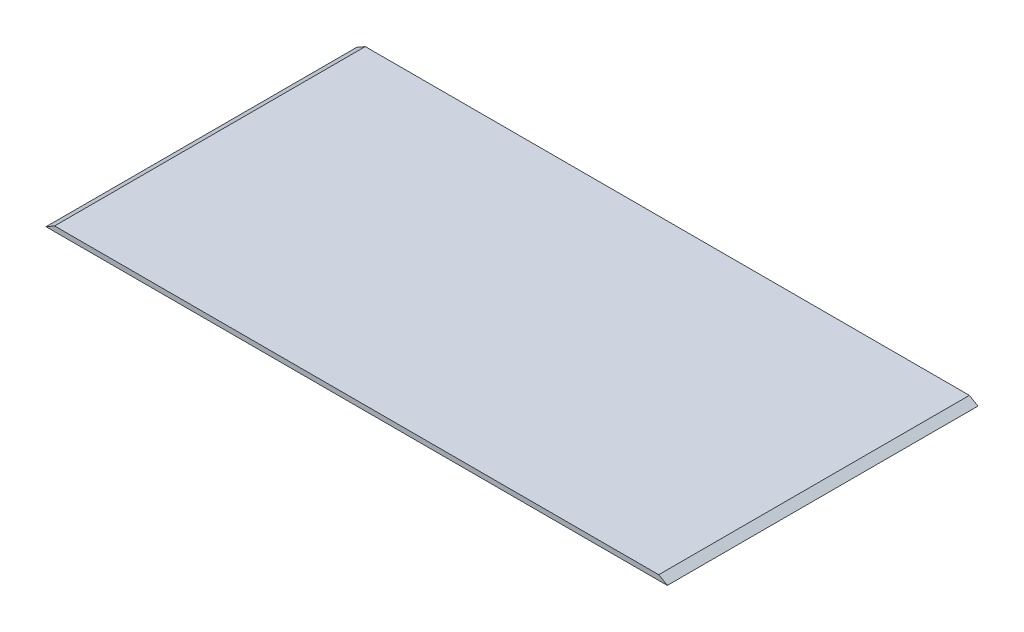
SolidWorks part; units mm, degrees
ref_plane "前视基准面" through (0, 0, 0) normal (0, 0, 1) x (1, 0, 0)
ref_plane "上视基准面" through (0, 0, 0) normal (0, 1, 0) x (1, 0, 0)
ref_plane "右视基准面" through (0, 0, 0) normal (1, 0, 0) x (0, 0, -1)
sketch "草图1" plane through (0, 0, 0) normal (0, 1, 0) x (1, 0, 0)
  line L1 (-125, -125) -> (125, -125)
  line L2 (-125, -125) -> (-125, 125)
  line L3 (-125, 125) -> (125, 125)
  line L4 (125, -125) -> (125, 125)
  line L5 (-125, -125) -> (125, 125) construction
  line L6 (-125, 125) -> (125, -125) construction
  point P0 (0, 0)
  dimension "D1" = 250
  dimension "D2" = 250
extrude "凸台-拉伸1" add sketch "草图1" along normal blind 2
sketch "草图2" plane through (0, 2, 0) normal (0, 1, 0) x (1, 0, 0)
  line L0 (-125, 0) -> (125, 0)
  line L4 (125, -125) -> (125, 125)
  line L5 (125, 125) -> (-125, 125)
  line L6 (-125, 125) -> (-125, -125)
  line L7 (-125, -125) -> (125, -125)
  line L8 (125, -125) -> (125, 0)
  line L10 (-125, 0) -> (-125, -125)
  line L11 (-125, -125) -> (125, -125)
  dimension "D1" = 0
extrude "切除-拉伸1" cut sketch "草图2" against normal up to surface (2 mm away) up to face at (0, 0, 0)
sketch "草图5" plane through (0, 0, 0) normal (0, -1, 0) x (1, 0, 0)
  line L0 (-0.2534, 0.2967) -> (-0.2534, -174.2192)
  line L1 (-125.2534, 0.2967) -> (124.7466, 0.2967)
  line L2 (-125.2534, 0.2967) -> (-125.2534, -124.7033)
  line L3 (-125.2534, -124.7033) -> (124.7466, -124.7033)
  line L4 (124.7466, 0.2967) -> (124.7466, -124.7033)
  line L5 (-125.2534, 0.2967) -> (-105.2534, 0.2967)
  line L6 (-125.2534, 0.2967) -> (-125.2534, -19.7033)
  line L7 (-125.2534, -19.7033) -> (-105.2534, -19.7033)
  line L8 (-105.2534, 0.2967) -> (-105.2534, -19.7033)
  line L9 (-125.2534, -124.7033) -> (-105.2534, -124.7033)
  line L10 (-125.2534, -124.7033) -> (-125.2534, -104.7033)
  line L11 (-125.2534, -104.7033) -> (-105.2534, -104.7033)
  line L12 (-105.2534, -124.7033) -> (-105.2534, -104.7033)
  line L13 (-110.2534, -14.7033) -> (-100.2534, -14.7033)
  line L14 (-110.2534, -14.7033) -> (-110.2534, -24.7033)
  line L15 (-110.2534, -24.7033) -> (-100.2534, -24.7033)
  line L16 (-100.2534, -14.7033) -> (-100.2534, -24.7033)
  line L17 (-110.2534, -14.7033) -> (-100.2534, -24.7033) construction
  line L18 (-110.2534, -24.7033) -> (-100.2534, -14.7033) construction
  line L19 (-110.2534, -99.7033) -> (-100.2534, -99.7033)
  line L20 (-110.2534, -99.7033) -> (-110.2534, -109.7033)
  line L21 (-110.2534, -109.7033) -> (-100.2534, -109.7033)
  line L22 (-100.2534, -99.7033) -> (-100.2534, -109.7033)
  line L23 (-110.2534, -99.7033) -> (-100.2534, -109.7033) construction
  line L24 (-110.2534, -109.7033) -> (-100.2534, -99.7033) construction
  line L25 (112.2466, -112.2033) -> (97.2466, -97.2033) construction
  line L26 (112.2466, -97.2033) -> (97.2466, -112.2033) construction
  line L27 (114.7466, -29.7033) -> (94.7466, -9.7033) construction
  line L28 (114.7466, -9.7033) -> (94.7466, -29.7033) construction
  line L29 (-115.2534, -9.7033) -> (-95.2534, -9.7033)
  line L30 (-115.2534, -9.7033) -> (-115.2534, -29.7033)
  line L31 (-115.2534, -29.7033) -> (-95.2534, -29.7033)
  line L32 (-95.2534, -9.7033) -> (-95.2534, -29.7033)
  line L33 (-115.2534, -9.7033) -> (-95.2534, -29.7033) construction
  line L34 (-115.2534, -29.7033) -> (-95.2534, -9.7033) construction
  line L35 (-112.7534, -97.2033) -> (-97.7534, -97.2033)
  line L36 (-112.7534, -97.2033) -> (-112.7534, -112.2033)
  line L37 (-112.7534, -112.2033) -> (-97.7534, -112.2033)
  line L38 (-97.7534, -97.2033) -> (-97.7534, -112.2033)
  line L39 (-112.7534, -97.2033) -> (-97.7534, -112.2033) construction
  line L40 (-112.7534, -112.2033) -> (-97.7534, -97.2033) construction
  line L41 (109.7466, -109.7033) -> (99.7466, -99.7033) construction
  line L42 (109.7466, -99.7033) -> (99.7466, -109.7033) construction
  line L43 (109.7466, -24.7033) -> (99.7466, -14.7033) construction
  line L44 (109.7466, -14.7033) -> (99.7466, -24.7033) construction
  line L45 (97.2466, -97.2033) -> (97.2466, -112.2033)
  line L46 (112.2466, -112.2033) -> (97.2466, -112.2033)
  line L47 (112.2466, -97.2033) -> (112.2466, -112.2033)
  line L48 (112.2466, -97.2033) -> (97.2466, -97.2033)
  line L49 (94.7466, -9.7033) -> (94.7466, -29.7033)
  line L50 (114.7466, -29.7033) -> (94.7466, -29.7033)
  line L51 (114.7466, -9.7033) -> (114.7466, -29.7033)
  line L52 (114.7466, -9.7033) -> (94.7466, -9.7033)
  line L53 (99.7466, -99.7033) -> (99.7466, -109.7033)
  line L54 (109.7466, -109.7033) -> (99.7466, -109.7033)
  line L55 (109.7466, -99.7033) -> (109.7466, -109.7033)
  line L56 (109.7466, -99.7033) -> (99.7466, -99.7033)
  line L57 (99.7466, -14.7033) -> (99.7466, -24.7033)
  line L58 (109.7466, -24.7033) -> (99.7466, -24.7033)
  line L59 (109.7466, -14.7033) -> (109.7466, -24.7033)
  line L60 (109.7466, -14.7033) -> (99.7466, -14.7033)
  line L61 (104.7466, -124.7033) -> (104.7466, -104.7033)
  line L62 (124.7466, -104.7033) -> (104.7466, -104.7033)
  line L63 (124.7466, -124.7033) -> (124.7466, -104.7033)
  line L64 (124.7466, -124.7033) -> (104.7466, -124.7033)
  line L65 (104.7466, 0.2967) -> (104.7466, -19.7033)
  line L66 (124.7466, -19.7033) -> (104.7466, -19.7033)
  line L67 (124.7466, 0.2967) -> (124.7466, -19.7033)
  line L68 (124.7466, 0.2967) -> (104.7466, 0.2967)
  line L69 (124.7466, 0.2967) -> (124.7466, -124.7033)
sketch "草图6" plane through (0, 0, 0) normal (0, -1, 0) x (1, 0, 0)
  line L1 (-110.2534, -14.7033) -> (-100.2534, -14.7033)
  line L2 (-110.2534, -14.7033) -> (-110.2534, -24.7033)
  line L3 (-110.2534, -24.7033) -> (-100.2534, -24.7033)
  line L4 (-100.2534, -14.7033) -> (-100.2534, -24.7033)
  line L5 (-110.2534, -99.7033) -> (-100.2534, -99.7033)
  line L6 (-110.2534, -99.7033) -> (-110.2534, -109.7033)
  line L7 (-110.2534, -109.7033) -> (-100.2534, -109.7033)
  line L8 (-100.2534, -99.7033) -> (-100.2534, -109.7033)
  line L9 (99.7466, -14.7033) -> (109.7466, -14.7033)
  line L10 (99.7466, -14.7033) -> (99.7466, -24.7033)
  line L11 (99.7466, -24.7033) -> (109.7466, -24.7033)
  line L12 (109.7466, -14.7033) -> (109.7466, -24.7033)
  line L13 (99.7466, -99.7033) -> (109.7466, -99.7033)
  line L14 (99.7466, -99.7033) -> (99.7466, -109.7033)
  line L15 (99.7466, -109.7033) -> (109.7466, -109.7033)
  line L16 (109.7466, -99.7033) -> (109.7466, -109.7033)
extrude "凸台-拉伸3" add sketch "草图6" along normal blind 10
sketch "草图7" plane through (0, 0, -125) normal (0, 0, -1) x (-1, 0, 0)
  line L0 (-125, 2) -> (-125, 0)
  line L1 (-125, 0) -> (-121.5359, 2)
  line L2 (-125, 2) -> (125, 2) construction
  line L3 (-121.5359, 2) -> (-125, 2)
  line L4 (121.5359, 2) -> (125, 2)
  line L5 (125, 2) -> (125, 0)
  line L6 (125, 0) -> (121.5359, 2)
  dimension "D1" = 30
  dimension "D2" = 30
extrude "切除-拉伸2" cut sketch "草图7" against normal through all
sketch "草图8" plane through (0, 0, 0) normal (1, 0, 0) x (0, 0, -1)
  line L0 (125, 2) -> (125, 0)
  line L1 (125, 0) -> (121.5359, 2)
  line L2 (0, 2) -> (125, 2) construction
  line L3 (121.5359, 2) -> (125, 2)
  dimension "D1" = 30
